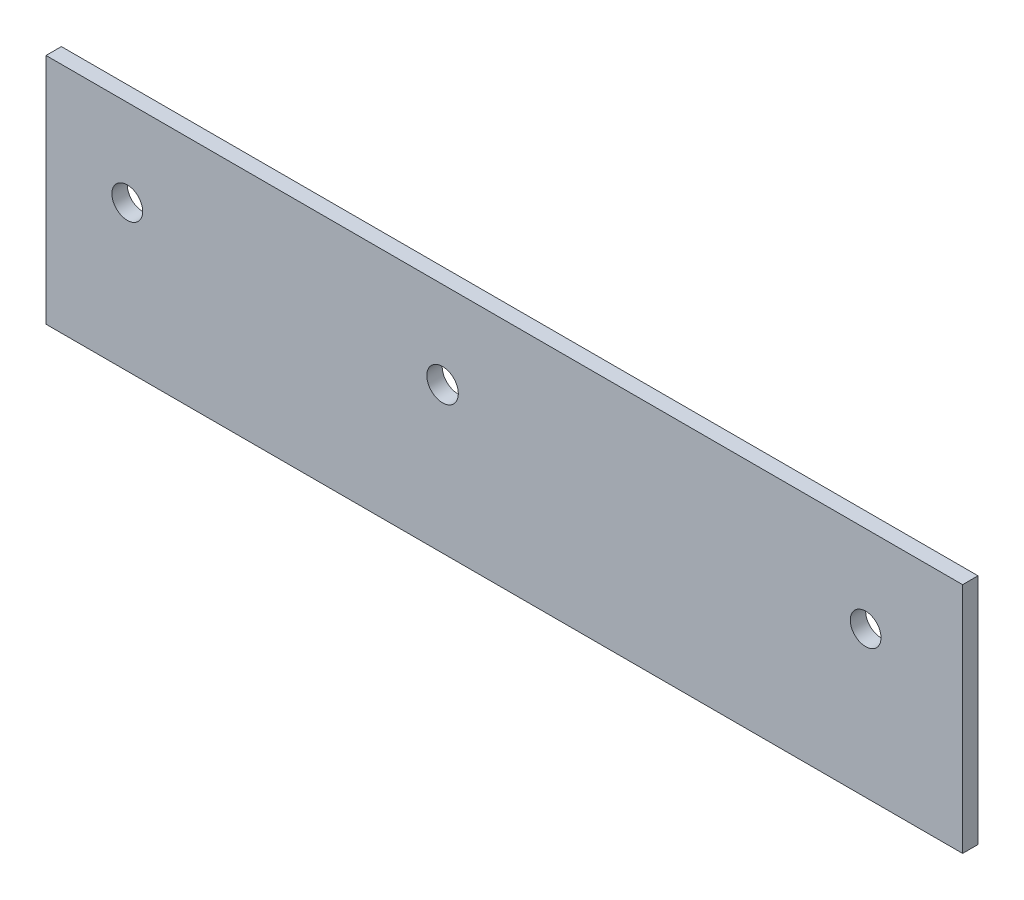
SolidWorks part; units mm, degrees
ref_plane "Front Plane" through (0, 0, 0) normal (0, 0, 1) x (1, 0, 0)
ref_plane "Top Plane" through (0, 0, 0) normal (0, 1, 0) x (1, 0, 0)
ref_plane "Right Plane" through (0, 0, 0) normal (1, 0, 0) x (0, 0, -1)
sketch "Sketch1" plane through (0, 0, 0) normal (0, 0, 1) x (1, 0, 0)
  line L1 (59.4232, 17.9178) -> (248.6172, 17.9178)
  line L2 (59.4232, 17.9178) -> (59.4232, -30.1304)
  line L3 (59.4232, -30.1304) -> (248.6172, -30.1304)
  line L4 (248.6172, 17.9178) -> (248.6172, -30.1304)
  circle A0 centre (76.2, 0) radius 3.175
  circle A1 centre (228.6, 0) radius 3.175
  circle A2 centre (141.2748, 0) radius 3.2512
  circle A4 centre (141.2748, 0) radius 3.175 construction
  dimension "D1" = 6.5024
extrude "Boss-Extrude1" add sketch "Sketch1" along normal blind 3.175
